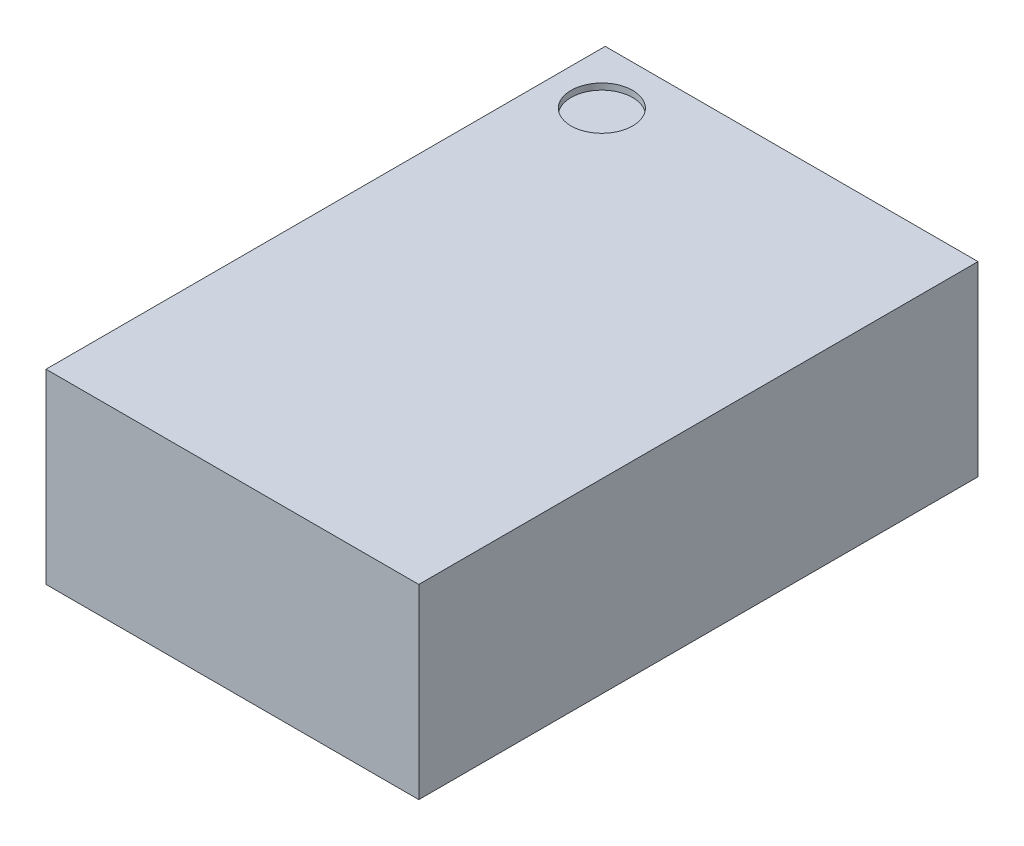
SolidWorks part; units mm, degrees
ref_plane "Front Plane" through (0, 0, 0) normal (0, 0, 1) x (1, 0, 0)
ref_plane "Top Plane" through (0, 0, 0) normal (0, 1, 0) x (1, 0, 0)
ref_plane "Right Plane" through (0, 0, 0) normal (1, 0, 0) x (0, 0, -1)
sketch "Sketch1" plane through (0, 0, 0) normal (0, 1, 0) x (1, 0, 0)
  line L1 (-0.75, -1.125) -> (0.75, -1.125)
  line L2 (-0.75, -1.125) -> (-0.75, 1.125)
  line L3 (-0.75, 1.125) -> (0.75, 1.125)
  line L4 (0.75, -1.125) -> (0.75, 1.125)
  line L5 (-0.75, -1.125) -> (0.75, 1.125) construction
  line L6 (-0.75, 1.125) -> (0.75, -1.125) construction
  point P0 (0, 0)
  dimension "D1" = 1.5
  dimension "D2" = 2.25
extrude "Boss-Extrude1" add sketch "Sketch1" along normal blind 0.75
sketch "Sketch2" plane through (0, 0.75, 0) normal (0, 1, 0) x (1, 0, 0)
  circle A0 centre (-0.5414, 0.9029) radius 0.124
extrude "Cut-Extrude1" cut sketch "Sketch2" against normal blind 0.025 contours A0
sketch "Sketch3" plane through (0, 0, 0) normal (0, -1, 0) x (1, 0, 0)
  line L0 (0, 1.2401) -> (0, -1.5851) construction
  line L1 (0.15, 1.05) -> (0.65, 1.05)
  line L2 (0.15, 1.05) -> (0.15, 0.35)
  line L3 (0.15, 0.35) -> (0.65, 0.35)
  line L4 (0.65, 1.05) -> (0.65, 0.35)
  line L5 (-0.65, 1.05) -> (-0.15, 1.05)
  line L6 (-0.65, 1.05) -> (-0.65, 0.35)
  line L7 (-0.65, 0.35) -> (-0.15, 0.35)
  line L8 (-0.15, 1.05) -> (-0.15, 0.35)
  line L9 (-0.75, 1.125) -> (0.75, 1.125) construction
  line L10 (0.11, 0.01) -> (0.11, -0.2)
  line L11 (-0.71, 0.01) -> (-0.11, 0.01)
  line L12 (-0.71, 0.01) -> (-0.71, -0.2)
  line L13 (-0.71, -0.2) -> (-0.11, -0.2)
  line L14 (-0.11, 0.01) -> (-0.11, -0.2)
  line L15 (0.11, 0.01) -> (0.71, 0.01)
  line L16 (0.71, 0.01) -> (0.71, -0.2)
  line L17 (0.11, -0.2) -> (0.71, -0.2)
  line L18 (0.11, -0.42) -> (0.11, -0.63)
  line L19 (0.11, -0.42) -> (0.71, -0.42)
  line L20 (0.71, -0.42) -> (0.71, -0.63)
  line L21 (0.11, -0.63) -> (0.71, -0.63)
  line L22 (0.11, -0.85) -> (0.11, -1.06)
  line L23 (0.11, -0.85) -> (0.71, -0.85)
  line L24 (0.71, -0.85) -> (0.71, -1.06)
  line L25 (0.11, -1.06) -> (0.71, -1.06)
  line L26 (-0.71, -0.42) -> (-0.71, -0.63)
  line L27 (-0.71, -0.42) -> (-0.11, -0.42)
  line L28 (-0.11, -0.42) -> (-0.11, -0.63)
  line L29 (-0.71, -0.63) -> (-0.11, -0.63)
  line L30 (-0.71, -0.85) -> (-0.71, -1.06)
  line L31 (-0.71, -0.85) -> (-0.11, -0.85)
  line L32 (-0.11, -0.85) -> (-0.11, -0.929)
  line L33 (-0.71, -1.06) -> (-0.215, -1.06)
  line L34 (-0.11, -0.929) -> (-0.215, -1.06)
  dimension "D1" = 0.5
  dimension "D2" = 0.7
  dimension "D3" = 0.3
  dimension "D4" = 0.15
  dimension "D5" = 0.075
  dimension "D6" = 0.21
  dimension "D7" = 0.6
  dimension "D8" = 0.11
  dimension "D9" = 0.34
  dimension "D12" = 0.7
  dimension "D10" = 2
  dimension "D11" = 3
extrude "Boss-Extrude2" add sketch "Sketch3" along normal blind 0.01
